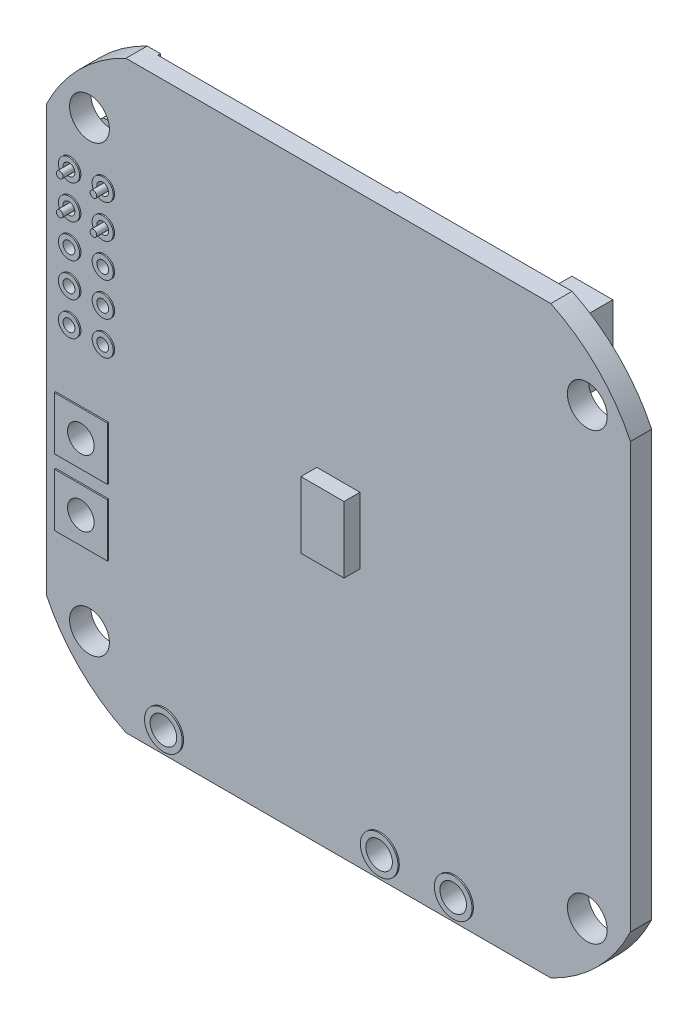
SolidWorks part; units mm, degrees
material "6061-T6 (SS)"
ref_plane "Alzado" through (0, 0, 0) normal (0, 0, 1) x (1, 0, 0)
ref_plane "Planta" through (0, 0, 0) normal (0, 1, 0) x (1, 0, 0)
ref_plane "Vista lateral" through (0, 0, 0) normal (1, 0, 0) x (0, 0, -1)
sketch "Croquis1" plane through (0, 0, 0) normal (0, 0, 1) x (1, 0, 0)
  line L0 (-22, 16) -> (-22, -16)
  line L1 (0, 0) -> (0, -6.2515) construction
  line L2 (22, 16) -> (22, -16)
  line L3 (-16, -22) -> (16, -22)
  line L4 (0, 0) -> (8.2976, 0) construction
  line L5 (-16, 22) -> (16, 22)
  arc A0 (-16, 22) -> (-22, 16) centre (-10.4982, 10.4982) ccw
  arc A2 (16, -22) -> (22, -16) centre (10.4982, -10.4982) ccw
  arc A3 (-22, -16) -> (-16, -22) centre (-10.4982, -10.4982) ccw
  arc A7 (22, 16) -> (16, 22) centre (10.4982, 10.4982) ccw
  point P0 (0, 0)
  point P4 (-22, 0)
  point P13 (0, -22)
  dimension "D3" = 25.5
  dimension "D4" = 32
  dimension "D1" = 32
  dimension "D2" = 22
  dimension "D5" = 22
extrude "Saliente-Extruir1" add sketch "Croquis1" along normal mid plane 1.6
sketch "Croquis2" plane through (0, 0, 0.8) normal (0, 0, 1) x (1, 0, 0)
  line L1 (18.75, -16.75) -> (-18.75, -16.75) construction
  line L2 (18.75, -16.75) -> (18.75, 16.75) construction
  line L3 (18.75, 16.75) -> (-18.75, 16.75) construction
  line L4 (-18.75, -16.75) -> (-18.75, 16.75) construction
  line L5 (18.75, -16.75) -> (-18.75, 16.75) construction
  line L6 (18.75, 16.75) -> (-18.75, -16.75) construction
  circle A0 centre (-18.75, 16.75) radius 1.5
  circle A1 centre (18.75, 16.75) radius 1.5
  circle A2 centre (18.75, -16.75) radius 1.5
  circle A3 centre (-18.75, -16.75) radius 1.5
  point P0 (0, 0)
  dimension "D1" = 3
  dimension "D2" = 37.5
  dimension "D3" = 33.5
extrude "Cortar-Extruir1" cut sketch "Croquis2" against normal through all
sketch "Croquis3" plane through (0, 0, 0.8) normal (0, 0, 1) x (1, 0, 0)
  line L1 (-1.625, 2.5) -> (1.625, 2.5)
  line L2 (-1.625, 2.5) -> (-1.625, -2.5)
  line L3 (-1.625, -2.5) -> (1.625, -2.5)
  line L4 (1.625, 2.5) -> (1.625, -2.5)
  line L5 (-1.625, 2.5) -> (1.625, -2.5) construction
  line L6 (-1.625, -2.5) -> (1.625, 2.5) construction
  point P0 (0, 0)
  dimension "D1" = 5
  dimension "D2" = 3.25
extrude "Saliente-Extruir2" add sketch "Croquis3" along normal blind 1.2
sketch "Croquis4" plane through (0, 0, -0.8) normal (0, 0, -1) x (-1, 0, 0)
  line L0 (22, 16) -> (22, -16) construction
  line L1 (-16, 22) -> (16, 22) construction
  circle A0 centre (17.653, 12.7) radius 0.445
  circle A1 centre (20.193, 12.7) radius 0.445
  circle A2 centre (20.193, 10.16) radius 0.445
  circle A3 centre (20.193, 7.62) radius 0.445
  circle A4 centre (20.193, 5.08) radius 0.445
  circle A5 centre (20.193, 2.54) radius 0.445
  circle A6 centre (17.653, 10.16) radius 0.445
  circle A7 centre (17.653, 7.62) radius 0.445
  circle A8 centre (17.653, 5.08) radius 0.445
  circle A9 centre (17.653, 2.54) radius 0.445
  dimension "D1" = 0.89
  dimension "D3" = 1.807
  dimension "D4" = 9.3
  dimension "D5" = 2.54
  dimension "D2" = 5
extrude "Cortar-Extruir2" cut sketch "Croquis4" against normal through all
sketch "Croquis5" plane through (0, 0, 0) normal (0, 0, 1) x (1, 0, 0)
  line L0 (-16, -22) -> (16, -22) construction
  line L1 (-17.3, -2.4) -> (-21.3, -2.4)
  line L2 (-17.3, -2.4) -> (-17.3, -6.4)
  line L3 (-17.3, -6.4) -> (-21.3, -6.4)
  line L4 (-21.3, -2.4) -> (-21.3, -6.4)
  line L5 (-17.3, -2.4) -> (-21.3, -6.4) construction
  line L6 (-17.3, -6.4) -> (-21.3, -2.4) construction
  line L7 (-17.3, -7.4) -> (-21.3, -7.4)
  line L8 (-17.3, -7.4) -> (-17.3, -11.4)
  line L9 (-17.3, -11.4) -> (-21.3, -11.4)
  line L10 (-21.3, -7.4) -> (-21.3, -11.4)
  line L11 (-17.3, -7.4) -> (-21.3, -11.4) construction
  line L12 (-17.3, -11.4) -> (-21.3, -7.4) construction
  line L13 (-22, 16) -> (-22, -16) construction
  circle A0 centre (-17.653, 2.54) radius 0.7974
  circle A1 centre (-20.193, 2.54) radius 0.7974
  circle A2 centre (-20.193, 5.08) radius 0.7974
  circle A3 centre (-17.653, 5.08) radius 0.7974
  circle A4 centre (-17.653, 7.62) radius 0.7974
  circle A5 centre (-17.653, 10.16) radius 0.7974
  circle A6 centre (-20.193, 7.62) radius 0.7974
  circle A7 centre (-20.193, 10.16) radius 0.7974
  circle A8 centre (-17.653, 12.7) radius 0.7974
  circle A9 centre (-20.193, 12.7) radius 0.7974
  circle A10 centre (-17.653, 12.7) radius 0.445
  circle A11 centre (-20.193, 12.7) radius 0.445
  circle A12 centre (-20.193, 10.16) radius 0.445
  circle A13 centre (-17.653, 10.16) radius 0.445
  circle A14 centre (-17.653, 7.62) radius 0.445
  circle A15 centre (-20.193, 7.62) radius 0.445
  circle A16 centre (-20.193, 5.08) radius 0.445
  circle A17 centre (-17.653, 5.08) radius 0.445
  circle A18 centre (-17.653, 2.54) radius 0.445
  circle A19 centre (-20.193, 2.54) radius 0.445
  point P0 (-19.3, -4.4)
  point P5 (-19.3, -9.4)
  dimension "D1" = 4
  dimension "D2" = 4
  dimension "D3" = 5
  dimension "D4" = 4
  dimension "D5" = 4
  dimension "D6" = 12.6
  dimension "D7" = 2.7
extrude "Saliente-Extruir3" add sketch "Croquis5" along normal mid plane 1.8
sketch "Croquis6" plane through (0, 0, -0.9) normal (0, 0, -1) x (-1, 0, 0)
  line L0 (21.3, -2.4) -> (21.3, -6.4) construction
  line L1 (21.3, -7.4) -> (21.3, -11.4) construction
  circle A0 centre (19.3, -4.4) radius 1
  circle A1 centre (19.3, -9.4) radius 1
  point P6 (21.3, -4.4)
  point P9 (21.3, -9.4)
  dimension "D1" = 2
extrude "Cortar-Extruir3" cut sketch "Croquis6" against normal through all both and the other way through all
sketch "Croquis7" plane through (0, 0, -0.8) normal (0, 0, -1) x (-1, 0, 0)
  line L0 (16, -22) -> (-16, -22) construction
  line L1 (22, 16) -> (22, -16) construction
  circle A0 centre (-8.75, -20.32) radius 1
  circle A1 centre (-3.17, -20.32) radius 1
  circle A2 centre (13.08, -20.32) radius 1
  dimension "D1" = 2
  dimension "D2" = 1.68
  dimension "D3" = 5.58
  dimension "D4" = 16.25
  dimension "D5" = 8.92
extrude "Cortar-Extruir4" cut sketch "Croquis7" against normal blind 10
sketch "Croquis8" plane through (0, 0, -0.8) normal (0, 0, -1) x (-1, 0, 0)
  line L0 (-22, -16) -> (-22, 16) construction
  line L1 (-20.5, 12.95) -> (-17.5, 12.95)
  line L2 (-20.5, 12.95) -> (-20.5, 10.45)
  line L3 (-20.5, 10.45) -> (-17.5, 10.45)
  line L4 (-17.5, 12.95) -> (-17.5, 10.45)
  line L5 (-20.5, 9.95) -> (-17.5, 9.95)
  line L6 (-20.5, 9.95) -> (-20.5, 7.45)
  line L7 (-20.5, 7.45) -> (-17.5, 7.45)
  line L8 (-17.5, 9.95) -> (-17.5, 7.45)
  line L10 (-16, 22) -> (16, 22) construction
  point P8 (-19, 7.45)
  point P11 (-20.5, 11.7)
  point P12 (-20.5, 8.7)
  point P15 (-17.5, 11.7)
  dimension "D1" = 3
  dimension "D2" = 3
  dimension "D3" = 2.5
  dimension "D4" = 3
  dimension "D5" = 10.3
extrude "Saliente-Extruir4" add sketch "Croquis8" along normal blind 1.2
sketch "Croquis9" plane through (0, 0, -2) normal (0, 0, -1) x (-1, 0, 0)
  line L0 (-17.5, 12.95) -> (-20.5, 12.95) construction
  line L1 (-17.5, 7.45) -> (-17.5, 9.95) construction
  line L2 (-17.5, 10.45) -> (-17.5, 12.95) construction
  circle A0 centre (-19, 11.7) radius 0.75
  circle A1 centre (-19, 8.7) radius 0.75
  point P7 (-19, 12.95)
  point P10 (-17.5, 8.7)
  point P14 (-17.5, 11.7)
  dimension "D1" = 1.5
extrude "Saliente-Extruir5" add sketch "Croquis9" along normal blind 0.8
sketch "Croquis10" plane through (0, 0, -0.8) normal (0, 0, -1) x (-1, 0, 0)
  line L0 (-22, -16) -> (-22, 16) construction
  line L1 (-16, -14.25) -> (-11, -14.25)
  line L2 (-16, -14.25) -> (-16, -19.25)
  line L3 (-16, -19.25) -> (-11, -19.25)
  line L4 (-11, -14.25) -> (-11, -19.25)
  line L5 (16, -22) -> (-16, -22) construction
  line L6 (11.25, -12.2) -> (16.25, -12.2)
  line L7 (11.25, -12.2) -> (11.25, -17.2)
  line L8 (11.25, -17.2) -> (16.25, -17.2)
  line L9 (16.25, -12.2) -> (16.25, -17.2)
  line L10 (5.8877, -14.25) -> (10.8877, -14.25)
  line L11 (5.8877, -14.25) -> (5.8877, -19.25)
  line L12 (5.8877, -19.25) -> (10.8877, -19.25)
  line L13 (10.8877, -14.25) -> (10.8877, -19.25)
  line L14 (0.4343, -14.25) -> (5.4343, -14.25)
  line L15 (0.4343, -14.25) -> (0.4343, -19.25)
  line L16 (0.4343, -19.25) -> (5.4343, -19.25)
  line L17 (5.4343, -14.25) -> (5.4343, -19.25)
  line L18 (22, 16) -> (22, -16) construction
  line L19 (-4.9483, -12.2) -> (0.0517, -12.2)
  line L20 (-4.9483, -12.2) -> (-4.9483, -17.2)
  line L21 (-4.9483, -17.2) -> (0.0517, -17.2)
  line L22 (0.0517, -12.2) -> (0.0517, -17.2)
  line L23 (-10.5433, -12.2) -> (-5.5433, -12.2)
  line L24 (-10.5433, -12.2) -> (-10.5433, -17.2)
  line L25 (-10.5433, -17.2) -> (-5.5433, -17.2)
  line L26 (-5.5433, -12.2) -> (-5.5433, -17.2)
  dimension "D1" = 5
  dimension "D2" = 5
  dimension "D3" = 6
  dimension "D4" = 2.75
  dimension "D5" = 5
  dimension "D6" = 5
  dimension "D7" = 5
  dimension "D8" = 5
  dimension "D9" = 5
  dimension "D10" = 5
  dimension "D11" = 5.75
  dimension "D12" = 4.8
  dimension "D13" = 5
  dimension "D14" = 5
  dimension "D15" = 5
  dimension "D16" = 5
extrude "Saliente-Extruir6" add sketch "Croquis10" along normal blind 0.9
sketch "Croquis11" plane through (0, 0, -0.8) normal (0, 0, -1) x (-1, 0, 0)
  line L0 (-13.6529, -19.5225) -> (-10.4593, -19.5225)
  line L1 (-10.4593, -19.5225) -> (-9.8124, -18.8756)
  line L2 (-9.8124, -18.8756) -> (-7.529, -18.8756)
  line L3 (-7.529, -18.8756) -> (-7.1476, -19.257)
  line L4 (-7.1476, -19.257) -> (-7.1476, -21.3437)
  line L5 (-7.1476, -21.3437) -> (-7.529, -21.7251)
  line L6 (-7.529, -21.7251) -> (-13.8301, -21.7251)
  line L7 (-13.8301, -21.7251) -> (-14.1414, -21.4138)
  line L8 (-14.1414, -21.4138) -> (-14.1414, -20.011)
  line L9 (-14.1414, -20.011) -> (-13.6529, -19.5225)
  line L10 (8.1723, -19.5225) -> (11.1983, -19.5225)
  line L11 (11.1983, -19.5225) -> (12.0225, -18.6983)
  line L12 (12.0225, -18.6983) -> (14.2962, -18.6983)
  line L13 (14.2962, -18.6983) -> (14.7785, -19.1806)
  line L14 (14.7785, -19.1806) -> (14.7785, -21.2429)
  line L15 (14.7785, -21.2429) -> (14.2962, -21.7251)
  line L16 (14.2962, -21.7251) -> (7.9951, -21.7251)
  line L17 (7.9951, -21.7251) -> (7.6839, -21.4138)
  line L18 (7.6839, -21.4138) -> (7.6839, -20.011)
  line L19 (7.6839, -20.011) -> (8.1723, -19.5225)
  line L20 (2.2631, -20.011) -> (1.7746, -19.5225)
  line L21 (2.2631, -21.4138) -> (2.2631, -20.011)
  line L22 (1.9518, -21.7251) -> (2.2631, -21.4138)
  line L23 (-4.3493, -21.7251) -> (1.9518, -21.7251)
  line L24 (-4.7307, -21.3437) -> (-4.3493, -21.7251)
  line L25 (-4.7307, -19.257) -> (-4.7307, -21.3437)
  line L26 (-4.3493, -18.8756) -> (-4.7307, -19.257)
  line L27 (-2.0659, -18.8756) -> (-4.3493, -18.8756)
  line L28 (-1.4189, -19.5225) -> (-2.0659, -18.8756)
  line L29 (1.7746, -19.5225) -> (-1.4189, -19.5225)
  line L30 (-5.9391, -18.0693) -> (-5.9391, -23.1735) construction
  circle A0 centre (-8.75, -20.32) radius 1
  circle A1 centre (-3.17, -20.32) radius 1
  circle A2 centre (13.08, -20.32) radius 1
extrude "Saliente-Extruir7" add sketch "Croquis11" along normal blind 0.1
sketch "Croquis12" plane through (0, 0, -0.8) normal (0, 0, -1) x (-1, 0, 0)
  line L0 (-19.5752, -2.7898) -> (-13.4845, -8.8805)
  line L1 (-19.5752, -2.7898) -> (-13.4845, 3.301)
  line L2 (-13.4845, -8.8805) -> (-7.3937, -2.7898)
  line L3 (-13.4845, 3.301) -> (-7.3937, -2.7898)
  line L4 (16, -22) -> (-16, -22) construction
  dimension "D1" = 45
extrude "Saliente-Extruir8" add sketch "Croquis12" along normal blind 0.75
sketch "Croquis13" plane through (0, 0, -0.8) normal (0, 0, -1) x (-1, 0, 0)
  line L1 (-16.4217, 20.3319) -> (-13.3413, 20.3319)
  line L2 (-16.4217, 20.3319) -> (-16.4217, 15.0982)
  line L3 (-16.4217, 15.0982) -> (-13.3413, 15.0982)
  line L4 (-13.3413, 20.3319) -> (-13.3413, 15.0982)
extrude "Saliente-Extruir9" add sketch "Croquis13" along normal blind 2.65
sketch "Croquis14" plane through (0, 0, -0.8) normal (0, 0, -1) x (-1, 0, 0)
  line L1 (-12.0511, 17.4084) -> (-8.2311, 17.4084)
  line L2 (-12.0511, 17.4084) -> (-12.0511, 13.5884)
  line L3 (-12.0511, 13.5884) -> (-8.2311, 13.5884)
  line L4 (-8.2311, 17.4084) -> (-8.2311, 13.5884)
  dimension "D1" = 3.82
extrude "Saliente-Extruir10" add sketch "Croquis14" along normal blind 3
sketch "Croquis30" plane through (0, 0, 0.8) normal (0, 0, 1) x (1, 0, 0)
  circle A0 centre (-13.08, -20.32) radius 1.4199
  circle A1 centre (8.75, -20.32) radius 1.4199
  circle A2 centre (3.17, -20.32) radius 1.4199
  circle A3 centre (-13.08, -20.32) radius 1
  circle A4 centre (3.17, -20.32) radius 1
  circle A5 centre (8.75, -20.32) radius 1
extrude "Saliente-Extruir17" add sketch "Croquis30" along normal blind 0.1
sketch "Croquis29" plane through (0, 0, -0.8) normal (0, 0, -1) x (-1, 0, 0)
  line L0 (-16, 22) -> (16, 22) construction
  line L1 (10.5, 1.5) -> (14, 1.5)
  line L2 (10.5, 1.5) -> (10.5, 0)
  line L3 (10.5, 0) -> (14, 0)
  line L4 (14, 1.5) -> (14, 0)
  line L5 (10.5, -0.65) -> (14, -0.65)
  line L6 (10.5, -0.65) -> (10.5, -2.15)
  line L7 (10.5, -2.15) -> (14, -2.15)
  line L8 (14, -0.65) -> (14, -2.15)
  line L9 (2.75, 1.5) -> (6.25, 1.5)
  line L10 (2.75, 1.5) -> (2.75, 0)
  line L11 (2.75, 0) -> (6.25, 0)
  line L12 (6.25, 1.5) -> (6.25, 0)
  line L13 (22, 16) -> (22, -16) construction
  dimension "D1" = 3.5
  dimension "D2" = 1.5
  dimension "D3" = 0.65
  dimension "D4" = 3.5
  dimension "D5" = 20.5
  dimension "D6" = 11.5
  dimension "D7" = 7.75
extrude "Saliente-Extruir16" add sketch "Croquis29" along normal blind 0.5
chamfer "Chaflán1" distance 1 angle 45 4 edges at (12.0511, 17.4084, -2.3) (8.2311, 17.4084, -2.3) (12.0511, 13.5884, -2.3) (8.2311, 13.5884, -2.3)
sketch "Croquis31" plane through (0, 0, -0.8) normal (0, 0, -1) x (-1, 0, 0)
  line L0 (-16, 22) -> (16, 22) construction
  line L1 (-3, 22) -> (15, 22)
  line L2 (-3, 22) -> (-3, 2.65)
  line L3 (-3, 2.65) -> (15, 2.65)
  line L4 (15, 22) -> (15, 2.65)
  line L5 (22, 16) -> (22, -16) construction
  dimension "D1" = 19.35
  dimension "D2" = 18
  dimension "D3" = 7
extrude "Cortar-Extruir5" cut sketch "Croquis31" against normal blind 0.2
sketch "Croquis32" plane through (0, 0, -0.9) normal (0, 0, -1) x (-1, 0, 0)
  circle A0 centre (17.653, 12.7) radius 0.65
  circle A1 centre (20.193, 12.7) radius 0.65
  circle A2 centre (20.193, 10.16) radius 0.65
  circle A3 centre (17.653, 10.16) radius 0.65
  dimension "D1" = 1.3
extrude "Saliente-Extruir18" add sketch "Croquis32" along normal blind 1.6
sketch "Croquis33" plane through (0, 0, -0.9) normal (0, 0, 1) x (1, 0, 0)
  circle A0 centre (-20.193, 12.7) radius 0.25
  circle A1 centre (-17.653, 12.7) radius 0.25
  circle A2 centre (-17.653, 10.16) radius 0.25
  circle A3 centre (-20.193, 10.16) radius 0.25
  dimension "D1" = 0.5
extrude "Saliente-Extruir19" add sketch "Croquis33" along normal blind 2.5
sketch "Croquis34" plane through (0, 0, -2.5) normal (0, 0, -1) x (-1, 0, 0)
  line L0 (16.388, 13.4906) -> (16.388, 11.9202)
  line L1 (16.388, 11.9202) -> (16.8728, 11.435)
  line L2 (16.8728, 11.435) -> (18.4226, 11.435)
  line L3 (18.4226, 11.435) -> (18.918, 11.9094)
  line L4 (18.918, 11.9094) -> (18.918, 13.4906)
  line L5 (18.918, 13.4906) -> (18.4332, 13.965)
  line L6 (18.4332, 13.965) -> (16.8728, 13.965)
  line L7 (16.8728, 13.965) -> (16.388, 13.4906)
  line L8 (17.653, 12.7) -> (17.653, 14.4547) construction
  line L9 (17.653, 12.7) -> (15.9852, 12.7) construction
  line L10 (18.9656, 13.4906) -> (18.9656, 11.9202)
  line L11 (18.9656, 11.9202) -> (19.4505, 11.435)
  line L12 (19.4505, 11.435) -> (21.0002, 11.435)
  line L13 (21.0002, 11.435) -> (21.4956, 11.9094)
  line L14 (21.4956, 11.9094) -> (21.4956, 13.4906)
  line L15 (21.4956, 13.4906) -> (21.0108, 13.965)
  line L16 (21.0108, 13.965) -> (19.4505, 13.965)
  line L17 (19.4505, 13.965) -> (18.9656, 13.4906)
  line L18 (20.2306, 12.7) -> (20.2306, 14.4547) construction
  line L19 (20.2306, 12.7) -> (18.5628, 12.7) construction
  line L20 (18.9656, 10.9094) -> (18.9656, 9.339)
  line L21 (18.9656, 9.339) -> (19.4505, 8.8538)
  line L22 (19.4505, 8.8538) -> (21.0002, 8.8538)
  line L23 (21.0002, 8.8538) -> (21.4956, 9.3282)
  line L24 (21.4956, 9.3282) -> (21.4956, 10.9094)
  line L25 (21.4956, 10.9094) -> (21.0108, 11.3838)
  line L26 (21.0108, 11.3838) -> (19.4505, 11.3838)
  line L27 (19.4505, 11.3838) -> (18.9656, 10.9094)
  line L28 (20.2306, 10.1188) -> (20.2306, 11.8735) construction
  line L29 (20.2306, 10.1188) -> (18.5628, 10.1188) construction
  line L30 (16.388, 10.9094) -> (16.388, 9.339)
  line L31 (16.388, 9.339) -> (16.8728, 8.8538)
  line L32 (16.8728, 8.8538) -> (18.4226, 8.8538)
  line L33 (18.4226, 8.8538) -> (18.918, 9.3282)
  line L34 (18.918, 9.3282) -> (18.918, 10.9094)
  line L35 (18.918, 10.9094) -> (18.4332, 11.3838)
  line L36 (18.4332, 11.3838) -> (16.8728, 11.3838)
  line L37 (16.8728, 11.3838) -> (16.388, 10.9094)
  line L38 (17.653, 10.1188) -> (17.653, 11.8735) construction
  line L39 (17.653, 10.1188) -> (15.9852, 10.1188) construction
  circle A0 centre (17.653, 12.7) radius 0.65
  circle A1 centre (20.2306, 12.7) radius 0.64
  circle A2 centre (20.2306, 10.1188) radius 0.6641
  circle A3 centre (17.653, 10.1188) radius 0.64
  point P2 (17.653, 13.965)
  point P9 (18.918, 12.7)
  dimension "D1" = 2.53
  dimension "D2" = 2.53
  dimension "D3" = 2
  dimension "D4" = 2
extrude "Saliente-Extruir20" add sketch "Croquis34" along normal blind 3
